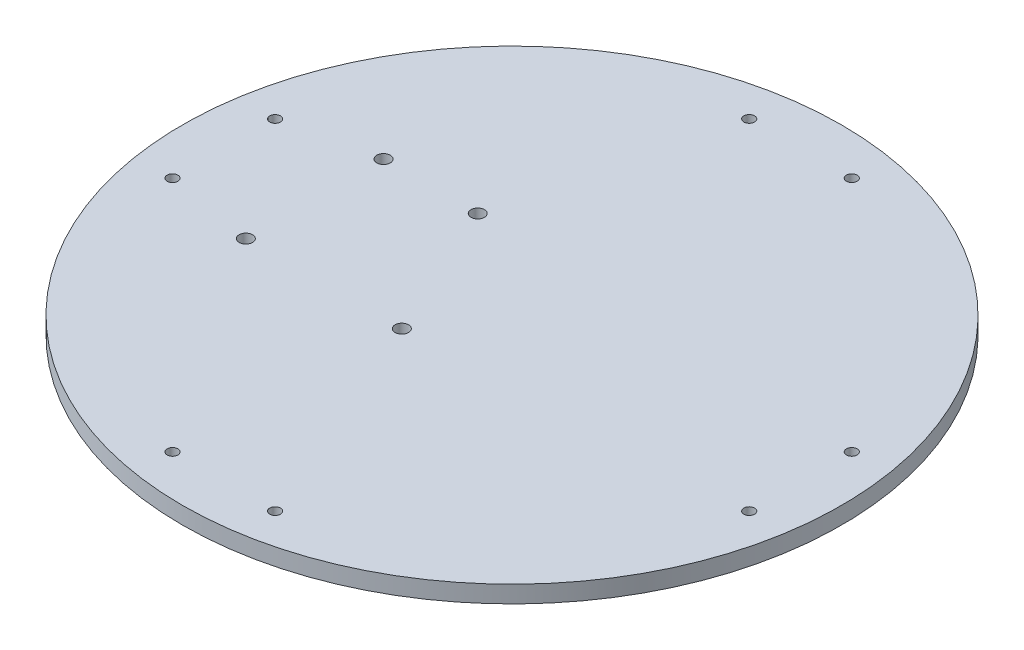
SolidWorks part; units mm, degrees
ref_plane "Front Plane" through (0, 0, 0) normal (0, 0, 1) x (1, 0, 0)
ref_plane "Top Plane" through (0, 0, 0) normal (0, 1, 0) x (1, 0, 0)
ref_plane "Right Plane" through (0, 0, 0) normal (1, 0, 0) x (0, 0, -1)
sketch "Sketch1" plane through (0, 0, 0) normal (0, 1, 0) x (1, 0, 0)
  circle A0 centre (0, 0) radius 122.4
  dimension "D1" = 244.8
extrude "Boss-Extrude1" add sketch "Sketch1" along normal blind 6.35
sketch "Sketch2" plane through (0, 6.35, 0) normal (0, 1, 0) x (1, 0, 0)
  line L0 (0, 122.4) -> (0, -122.4) construction
  line L1 (-122.4, 0) -> (122.4, 0) construction
  line L2 (-25.4, -119.7355) -> (25.4, -119.7355) construction
  circle A0 centre (0, 0) radius 122.4 construction
  circle A1 centre (-19.05, -107.0355) radius 1.9939
  circle A2 centre (19.05, -107.0355) radius 1.9939
  dimension "D2" = 3.9878
  dimension "D1" = 50.8
  dimension "D3" = 6.35
  dimension "D4" = 6.35
  dimension "D5" = 12.7
extrude "Cut-Extrude1" cut sketch "Sketch2" against normal through all
pattern_circular "CirPattern1" count 4 every 90 about axis through (0, 0, -0.0568) along (0, 1, 0) of "Cut-Extrude1"
sketch "Sketch3" plane through (0, 6.35, 0) normal (0, 1, 0) x (1, 0, 0)
  line L1 (-122.4, 0) -> (122.4, 0) construction
  circle A0 centre (-74.0546, 26.3358) radius 2.5
  circle A1 centre (-39.0546, 26.3358) radius 2.5
  circle A2 centre (-16.1134, -24.8087) radius 2.5
  circle A3 centre (-74.0546, -24.8087) radius 2.5
  point P11 (0, 0)
  point P12 (0, 0)
  point P13 (0, 0)
  point P14 (0, 0)
  point P15 (0, 0)
  dimension "D7" = 5
  dimension "D8" = 24.8087
  dimension "D1" = 35
  dimension "D2" = 57.9412
  dimension "D3" = 51.1446
  dimension "D5" = 74.0546
  dimension "D6" = 26.3358
  dimension "D9" = 22.9412
extrude "Cut-Extrude3" cut sketch "Sketch3" against normal through all
